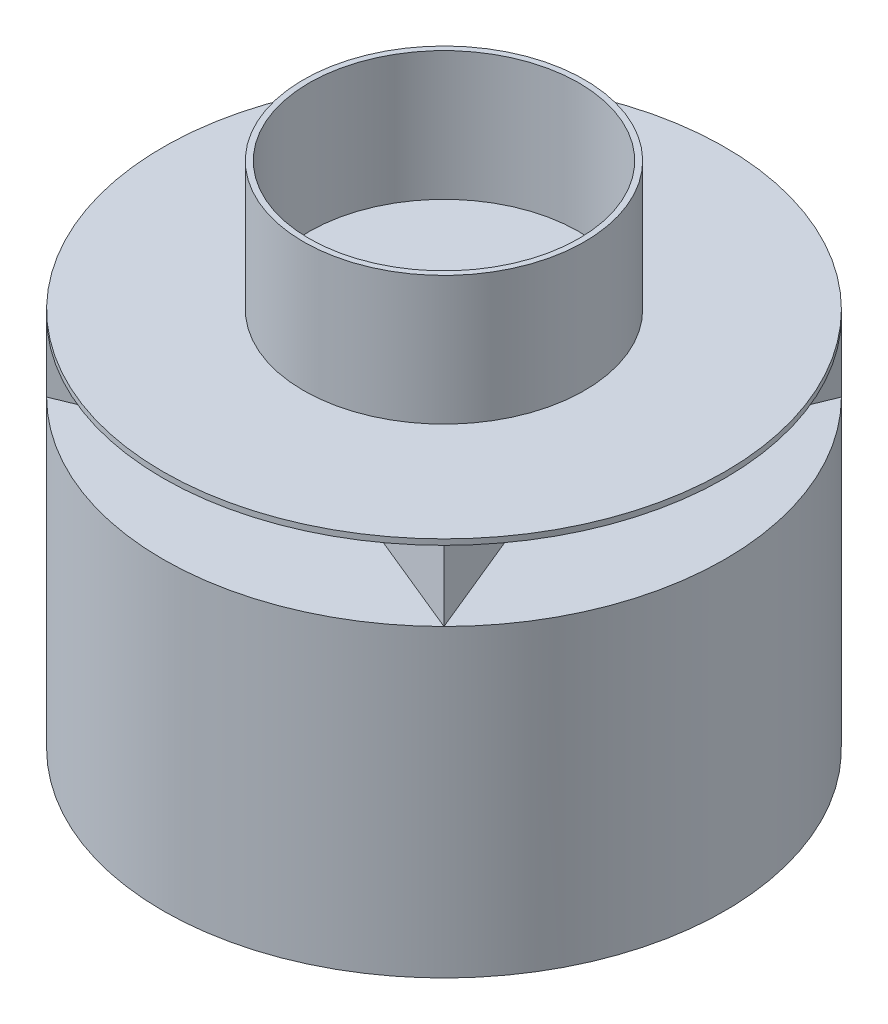
SolidWorks part; units mm, degrees
material "Plain Carbon Steel"
ref_plane "Front Plane" through (0, 0, 0) normal (0, 0, 1) x (1, 0, 0)
ref_plane "Top Plane" through (0, 0, 0) normal (0, 1, 0) x (1, 0, 0)
ref_plane "Right Plane" through (0, 0, 0) normal (1, 0, 0) x (0, 0, -1)
sketch "Sketch11" plane through (0, 0, 0) normal (0, 1, 0) x (1, 0, 0)
  circle A0 centre (0, 0) radius 304.8
extrude "Boss-Extrude5" add sketch "Sketch11" along normal blind 330.2
ref_plane "Plane3" through (0, 330.2, 0) normal (0, 1, 0) x (1, 0, 0)
sketch "Sketch12" plane through (0, 330.2, 0) normal (0, 1, 0) x (1, 0, 0)
  line L0 (-127, 0) -> (-215.5261, -215.5261)
  line L1 (127, 0) -> (215.5261, -215.5261)
  line L2 (-127, 0) -> (-215.5261, 215.5261)
  line L3 (-215.5261, -215.5261) -> (0, -127)
  line L4 (0, -127) -> (215.5261, -215.5261)
  line L5 (0, 127) -> (-215.5261, 215.5261)
  line L6 (0, 127) -> (215.5261, 215.5261)
  line L7 (215.5261, 215.5261) -> (127, 0)
  circle A0 centre (0, 0) radius 127
  circle A1 centre (0, 0) radius 304.8
extrude "Boss-Extrude6" add sketch "Sketch12" along normal blind 76.2 contours A0 | L4 A1 L3 A0
ref_plane "Plane4" through (0, 406.4, 0) normal (0, 1, 0) x (1, 0, 0)
sketch "Sketch13" plane through (0, 406.4, 0) normal (0, 1, 0) x (1, 0, 0)
  circle A0 centre (0, 0) radius 304.8
extrude "Boss-Extrude7" add sketch "Sketch13" along normal blind 6.096
ref_plane "Plane5" through (0, 412.496, 0) normal (0, 1, 0) x (1, 0, 0)
sketch "Sketch14" plane through (0, 412.496, 0) normal (0, 1, 0) x (1, 0, 0)
  circle A0 centre (0, 0) radius 152.4
  circle A1 centre (0, 0) radius 146.304
extrude "Boss-Extrude8" add sketch "Sketch14" along normal blind 139.7
ref_plane "Plane6" through (0, 412.496, 0) normal (0, 1, 0) x (1, 0, 0)
